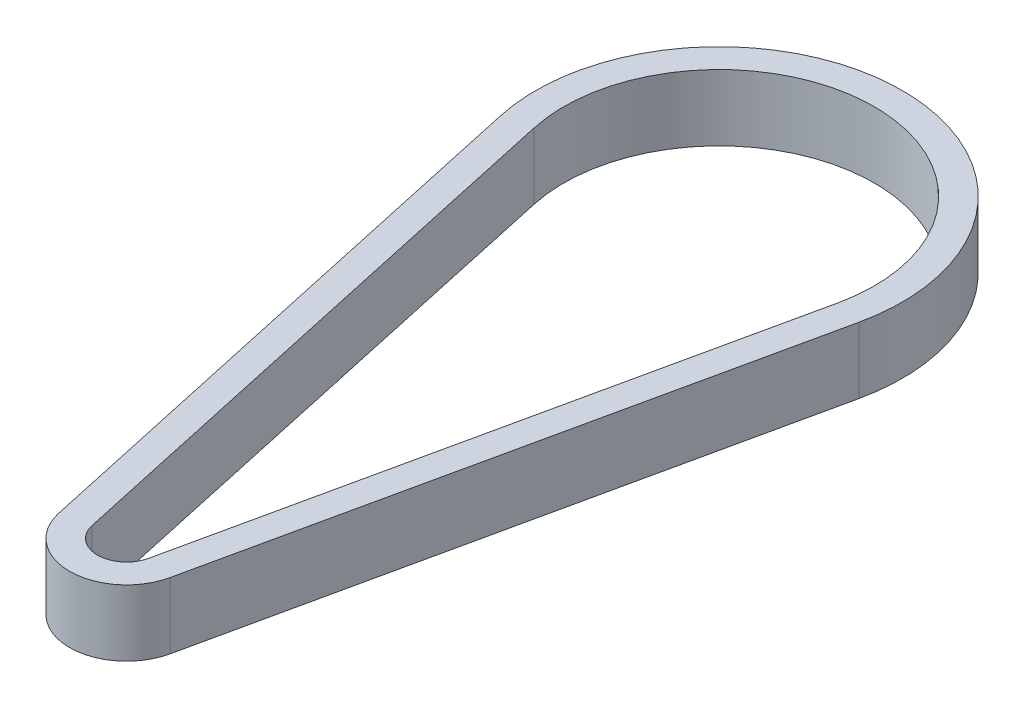
SolidWorks part; units mm, degrees
ref_plane "Front" through (0, 0, 0) normal (0, 0, 1) x (1, 0, 0)
ref_plane "Top" through (0, 0, 0) normal (0, 1, 0) x (1, 0, 0)
ref_plane "Right" through (0, 0, 0) normal (1, 0, 0) x (0, 0, -1)
sketch "Sketch1" plane through (0, 0, 0) normal (0, 1, 0) x (1, 0, 0)
  line L0 (0, 0) -> (0, -80.6615) construction
  line L1 (-5.598, -81.8825) -> (-22.3919, -4.8838)
  line L2 (5.598, -81.8825) -> (22.3919, -4.8838)
  circle A0 centre (0, 0) radius 22.9183 construction
  circle A1 centre (0, -80.6615) radius 5.7296 construction
  arc A2 (-22.3919, -4.8838) -> (22.3919, -4.8838) centre (0, 0) cw
  arc A3 (-5.598, -81.8825) -> (5.598, -81.8825) centre (0, -80.6615) ccw
  dimension "D1" = 11.4592
  dimension "D2" = 45.8366
sketch "Sketch2" plane through (0, 0, 0) normal (0, 1, 0) x (1, 0, 0)
  line L6 (7.5833, -82.3155) -> (24.3772, -5.3168)
  line L7 (-24.3772, -5.3168) -> (-7.5833, -82.3155)
  line L8 (3.8608, -81.5036) -> (20.6547, -4.5049)
  line L9 (-20.6547, -4.5049) -> (-3.8608, -81.5036)
  line L10 (3.8608, -81.5036) -> (20.6547, -4.5049)
  line L11 (-20.6547, -4.5049) -> (-3.8608, -81.5036)
  arc A6 (-7.5833, -82.3155) -> (7.5833, -82.3155) centre (0, -80.6615) ccw
  arc A7 (24.3772, -5.3168) -> (-24.3772, -5.3168) centre (0, 0) ccw
  arc A8 (-3.8608, -81.5036) -> (3.8608, -81.5036) centre (0, -80.6615) ccw
  arc A9 (20.6547, -4.5049) -> (-20.6547, -4.5049) centre (0, 0) ccw
  arc A10 (-3.8608, -81.5036) -> (3.8608, -81.5036) centre (0, -80.6615) ccw
  arc A11 (20.6547, -4.5049) -> (-20.6547, -4.5049) centre (0, 0) ccw
  dimension "D1" = 3.81
  dimension "D2" = 1.778
extrude "Boss-Extrude1" add sketch "Sketch2" along normal blind 9
equation "\"D1@Sketch1\"=3mm*12/pi"
equation "\"D2@Sketch1\"=48*3mm/pi"
equation "\"D3@Sketch1\"=3mm*85"
